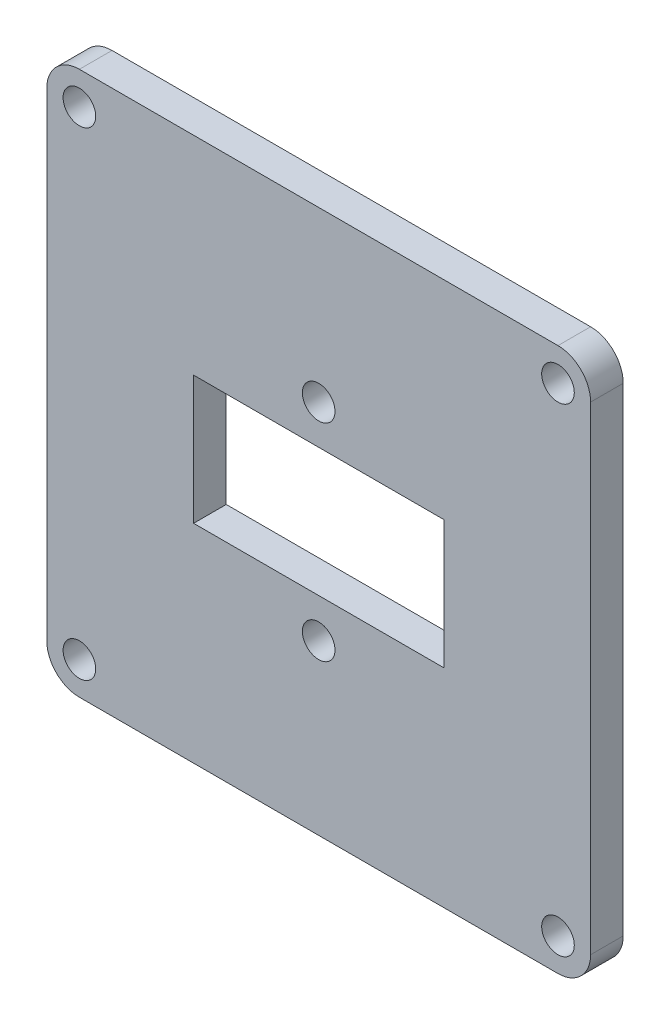
SolidWorks part; units mm, degrees
ref_plane "Plan de face" through (0, 0, 0) normal (0, 0, 1) x (1, 0, 0)
ref_plane "Plan de dessus" through (0, 0, 0) normal (0, 1, 0) x (1, 0, 0)
ref_plane "Plan de droite" through (0, 0, 0) normal (1, 0, 0) x (0, 0, -1)
sketch "Esquisse14" plane through (0, 0, 0) normal (0, 0, 1) x (1, 0, 0)
  line L0 (58.6876, -85.6153) -> (47.1876, -85.6153) construction
  line L1 (58.6876, -91.5153) -> (35.6876, -91.5153)
  line L2 (58.6876, -91.5153) -> (58.6876, -79.7153)
  line L3 (58.6876, -79.7153) -> (35.6876, -79.7153)
  line L4 (35.6876, -91.5153) -> (35.6876, -79.7153)
  line L5 (25.1876, -60.6153) -> (69.1876, -60.6153)
  line L6 (22.1876, -63.6153) -> (22.1876, -107.6153)
  line L7 (25.1876, -110.6153) -> (69.1876, -110.6153)
  line L8 (72.1876, -63.6153) -> (72.1876, -107.6153)
  circle A0 centre (47.1876, -76.1153) radius 1.5
  circle A1 centre (47.1876, -95.1153) radius 1.5
  arc A2 (22.1876, -107.6153) -> (25.1876, -110.6153) centre (25.1876, -107.6153) ccw
  arc A3 (69.1876, -110.6153) -> (72.1876, -107.6153) centre (69.1876, -107.6153) ccw
  arc A4 (69.1876, -60.6153) -> (72.1876, -63.6153) centre (69.1876, -63.6153) cw
  arc A5 (25.1876, -60.6153) -> (22.1876, -63.6153) centre (25.1876, -63.6153) ccw
  circle A6 centre (25.1876, -63.6153) radius 1.5
  circle A7 centre (25.1876, -107.6153) radius 1.5
  circle A8 centre (69.1876, -107.6153) radius 1.5
  circle A9 centre (69.1876, -63.6153) radius 1.5
  point P18 (72.1876, -110.6153)
  point P21 (72.1876, -60.6153)
  point P24 (22.1876, -60.6153)
  dimension "D8" = 3
  dimension "D9" = 3
  dimension "D10" = 19
  dimension "D11" = 9.5
  dimension "D12" = 3
  dimension "D13" = 3
  dimension "D14" = 3
  dimension "D15" = 3
  dimension "D16" = 3
  dimension "D1" = 11.8
  dimension "D2" = 23
  dimension "D3" = 50
  dimension "D4" = 50
  dimension "D5" = 13.5
  dimension "D6" = 25
  dimension "D7" = 11.5
extrude "Boss.-Extru.14" add sketch "Esquisse14" along normal blind 3 separate body
